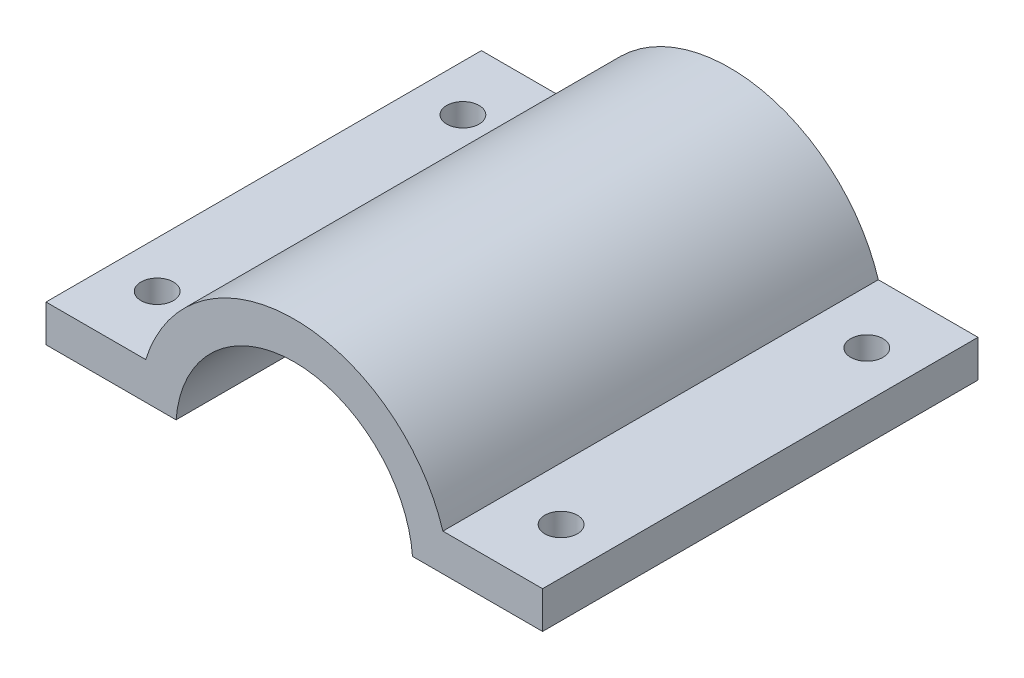
SolidWorks part; units mm, degrees
ref_plane "Front Plane" through (0, 0, 0) normal (1, 0, 0) x (0, 1, 0)
ref_plane "Top Plane" through (0, 0, 0) normal (0, 0, 1) x (0, 1, 0)
ref_plane "Right Plane" through (0, 0, 0) normal (0, 1, 0) x (-1, 0, 0)
sketch "Sketch1" plane through (0, 0, 0) normal (0, 0, 1) x (0, 1, 0)
  line L0 (1, 12.7609) -> (1, 26.8)
  line L1 (1, 26.8) -> (5, 26.8)
  line L2 (5, 26.8) -> (5, 16.0387)
  line L3 (5, -16.0387) -> (5, -26.8)
  line L4 (5, -26.8) -> (1, -26.8)
  line L5 (1, -26.8) -> (1, -12.7609)
  line L6 (0, 12.8) -> (-12.8, 12.8) construction
  line L7 (-12.8, 12.8) -> (-12.8, 0) construction
  line L8 (-12.8, 0) -> (-12.8, -12.7609) construction
  line L9 (-12.8, -12.7609) -> (1, -12.7609) construction
  line L10 (0, 16.8) -> (5, 16.8) construction
  circle A0 centre (0, 0) radius 12.8 construction
  arc A1 (5, 16.0387) -> (5, -16.0387) centre (0, 0) cw
  arc A2 (1, -12.7609) -> (1, 12.7609) centre (0, 0) ccw
  circle A3 centre (0, 0) radius 16.8 construction
  dimension "D1" = 25.6
  dimension "D2" = 4
  dimension "D3" = 10
  dimension "D4" = 4
  dimension "D5" = 1
extrude "Boss-Extrude1" add sketch "Sketch1" along normal blind 47
sketch "Sketch2" plane through (0, 5, 0) normal (0, 1, 0) x (-1, 0, 0)
  line L0 (-26.8, 23.5) -> (-16.0387, 23.5) construction
  line L1 (-26.8, 47) -> (-26.8, 0) construction
  line L2 (-16.0387, 47) -> (-16.0387, 0) construction
  line L3 (0, 47) -> (0, 0) construction
  line L4 (16.0387, 47) -> (-16.0387, 47) construction
  line L5 (-21.8, 40) -> (-21.8, 0) construction
  line L6 (-26.8, 47) -> (-16.0387, 47) construction
  line L7 (-26.8, 0) -> (-16.0387, 0) construction
  circle A0 centre (-21.8, 40) radius 1.75
  circle A1 centre (-21.8, 7) radius 1.75
  circle A2 centre (21.8, 7) radius 1.75
  circle A3 centre (21.8, 40) radius 1.75
  point P12 (0, 0)
  point P16 (0, 0)
  point P17 (-22.2609, 1.2836)
  point P27 (0, 0)
  point P28 (0, 0)
  dimension "D1" = 3.5
  dimension "D2" = 33
  dimension "D3" = 5
  dimension "D4" = 7
extrude "Cut-Extrude1" cut sketch "Sketch2" against normal up to next
